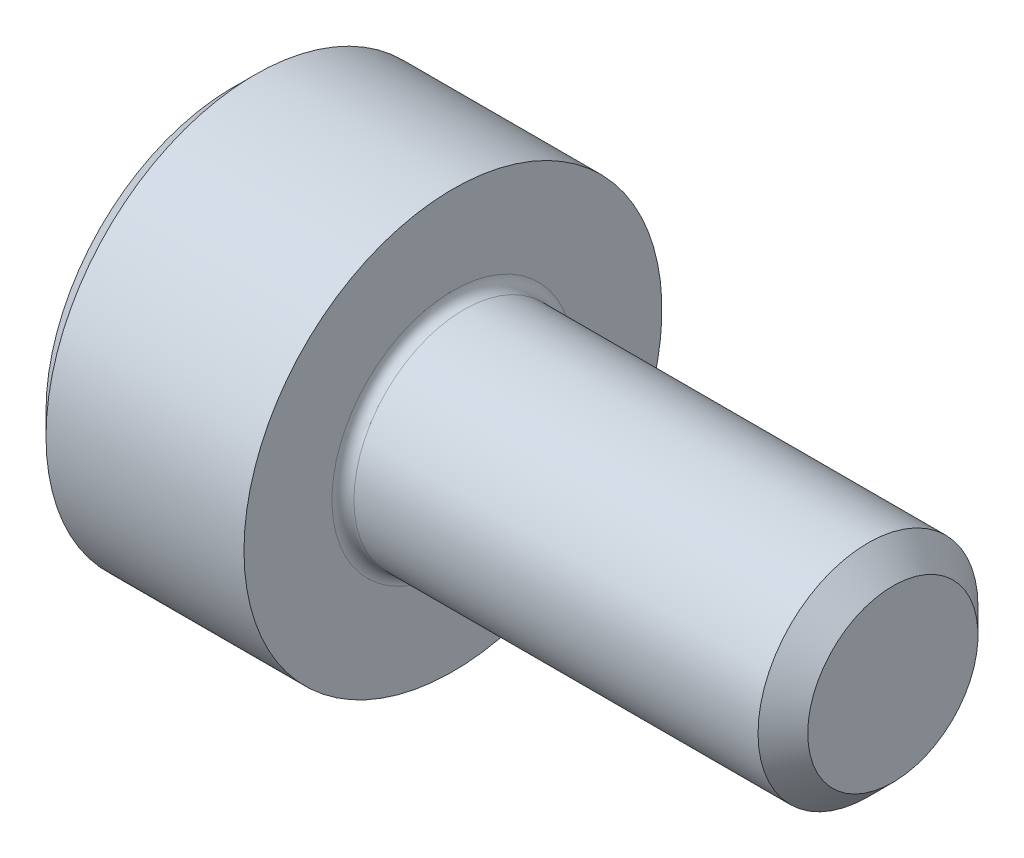
SolidWorks part; units mm, degrees
revolve "Base-Revolve" add sketch "BodySke"
sketch "BodySke" plane through (0, 0, 0) normal (0, 0, 1) x (1, 0, 0)
  line L0 (0, 0) -> (0, 1.7)
  line L1 (0.2, 1.9) -> (2, 1.9)
  line L2 (2, 1.9) -> (2, 1)
  line L3 (2, 1) -> (5.774, 1)
  line L4 (6, 0.774) -> (6, 0)
  line L5 (6, 0) -> (0, 0)
  line L6 (-31.75, 0) -> (127, 0) construction
  line L7 (0, 1.7) -> (0.2, 1.9)
  line L8 (6, 0.774) -> (5.774, 1)
  line L9 (0, -1.7) -> (0.2, -1.9) construction
  line L10 (6, -0.774) -> (5.774, -1) construction
  line L11 (2.4, 9.525) -> (2.4, 3.175) construction
  line L12 (2, 9.525) -> (2, 3.175) construction
  line L13 (-44, 9.525) -> (-44, 3.175) construction
  dimension "Diameter" = 2
  dimension "Head_ht" = 2
  dimension "Length" = 4
  dimension "Body_ch_ang" = 45
  dimension "Head_dia" = 3.8
  dimension "Head_ch_ang" = 45
  dimension "Minor_dia" = 1.548
  dimension "Advance" = 0.4
  dimension "Thread_nom" = 4
  dimension "Thread_length" = 50
  dimension "Head_ch_ht" = 0.2
cosmetic thread "ThreadCosmetic" [suppressed]
fillet "Fillet1" radius 0.1 1 edges at (2, 0, 1)
ref_plane "Plane1" through (0, 0, 0) normal (0, 0, 1) x (1, 0, 0)
ref_plane "Plane2" through (0, 0, 0) normal (0, 1, 0) x (1, 0, 0)
ref_plane "Plane3" through (0, 0, 0) normal (1, 0, 0) x (0, 0, -1)
sketch "Sketch2" plane through (0, 0, 0) normal (0, 0, 1) x (1, 0, 0)
  line L0 (0, 0.7725) -> (1, 0.7725)
  line L1 (1, 0.7725) -> (1.446, 0)
  line L2 (-31.75, 0) -> (127, 0) construction
  line L3 (1.446, 0) -> (0, 0)
  line L4 (0, 0) -> (0, 0.7725)
  line L5 (0, 1.7) -> (0, -1.7) construction
  line L6 (0, 0) -> (47.625, 0) construction
  line L7 (2, -1.9) -> (2, 1.9) construction
  dimension "D1" = 0.7725
  dimension "D2" = 60
revolve "Hex-PreBroach" cut sketch "Sketch2" angle 360 about L6
sketch "Sketch3" plane through (0, 0, 0) normal (-1, 0, 0) x (0, 0.5, 0.866)
  line L0 (0.446, 0.7725) -> (-0.446, 0.7725)
  line L1 (-0.446, 0.7725) -> (-0.892, 0)
  line L2 (0.446, 0.7725) -> (0.892, 0)
  line L3 (0.446, -0.7725) -> (0.892, 0)
  line L4 (0.446, -0.7725) -> (-0.446, -0.7725)
  line L5 (-0.446, -0.7725) -> (-0.892, 0)
  dimension "D1" = 0.7725
  dimension "D2" = 0.7725
  dimension "Hex_size" = 1.545
extrude "Hex" cut sketch "Sketch3" against normal blind 1
sketch "Sketch4" plane through (0, 0, 0) normal (-1, 0, 0) x (0, 0, 1)
  line L0 (0, 0) -> (0.9398, 0)
  line L1 (0, 0) -> (6.1484, 3.5498) construction
  line L2 (0, 0) -> (0.4699, 0.8139)
  line L3 (0.7832, 0.2175) -> (0.8962, 0.2828)
  line L4 (0.58, 0.5695) -> (0.693, 0.6348)
  arc A0 (0.7832, 0.2175) -> (0.58, 0.5695) centre (0, 0) ccw
  arc A1 (0.9398, 0) -> (0.8962, 0.2828) centre (0, 0) ccw
  arc A2 (0.4699, 0.8139) -> (0.693, 0.6348) centre (0, 0) cw
  dimension "D1" = 30
  dimension "D2" = 60
  dimension "Spline_p_dim" = 0.4064
  dimension "D3" = 0.2032
extrude "Spline" [suppressed] cut sketch "Sketch4" against normal blind 1
pattern_circular "CirPattern1" [suppressed] count 6 every 60
sketch "Sketch5" plane through (0, 0, 0) normal (0, 0, 1) x (1, 0, 0)
  line L0 (-31.75, 0) -> (127, 0) construction
  line L2 (0, 1.7) -> (0, -1.7) construction
  circle A0 centre (0.1, 0) radius 0.005
  dimension "Drilled_hole_dia" = 0.01
  dimension "Drilled_hole_loc" = 0.1
extrude "Hole" [suppressed] cut sketch "Sketch5" against normal through all and the other way through all
pattern_circular "Drilled-4" [suppressed] count 2 every 60
pattern_circular "Drilled-6" [suppressed] count 3 every 60
sketch "ThdSchSke" plane through (0, 0, 0) normal (0, 0, 1) x (1, 0, 0)
  line L0 (2.4, -0.774) -> (2.2418, -1)
  line L1 (2.4, -0.774) -> (2.5582, -1)
  line L2 (2.5582, -1) -> (2.5582, -1.25)
  line L3 (-3.175, 0) -> (5.1513, 0) construction
  line L5 (2.5582, -1.25) -> (2.2418, -1.25)
  line L6 (2.2418, -1.25) -> (2.2418, -1)
  line L7 (0, 1.7) -> (0, -1.7) construction
  dimension "Thread_minor" = 1.548
  dimension "Diameter" = 2
  dimension "Start" = 2.4
revolve "ThreadSchematic" [suppressed] cut sketch "ThdSchSke" angle 360 about L3
pattern_linear "ThdSchPat" [suppressed]
equation "\"D2@Sketch3\" = \"Hex_size@Sketch3\" / 2"
equation "\"D1@Sketch3\" = \"Hex_size@Sketch3\" / 2"
equation "\"D1@Sketch2\" = \"Hex_size@Sketch3\" / 2"
equation "\"D3@Sketch4\" = \"Spline_p_dim@Sketch4\" / 2"
equation "\"Thread_minor@ThreadCosmetic\"  =  \"Minor_dia@BodySke\""
equation "\"D2@CirPattern1\" = 360 / \"Num_teeth@CirPattern1\""
equation "\"Wall_thickness@Sketch2\" = \"Head_ht@BodySke\" - \"Key_eng@Hex\""
equation "\"Thread_length@ThreadCosmetic\" = ((sgn( (\"Length@BodySke\" - \"Advance@BodySke\" ) - \"Thread_nom@BodySke\" )-1)*( (\"Length@BodySke\" - \"Advance@BodySke\" ) - \"Thread_nom@BodySke\" ))/-2+ \"Thread_nom@BodySke\""
equation "\"Thread_minor@ThdSchSke\" = \"Minor_dia@BodySke\""
equation "\"Diameter@ThdSchSke\" = \"Diameter@BodySke\""
equation "\"Overcut@ThdSchSke\" = \"Diameter@BodySke\" * 1.25"
equation "\"Start@ThdSchSke\" = \"Head_ht@BodySke\" + \"Length@BodySke\" - \"Thread_length@ThreadCosmetic\"  '---Non-countersunk---"
equation "\"Num_threads@ThdSchPat\" = int( \"Thread_length@ThreadCosmetic\" / \"Advance@BodySke\" + 0.999 )  + 1"
equation "\"Advance@ThdSchPat\" = \"Thread_length@ThreadCosmetic\" /  (\"Num_threads@ThdSchPat\" - 1) 'relax it"
equation "\"Num_threads@ThdSchPat\" = \"Num_threads@ThdSchPat\" - sgn( \"Num_threads@ThdSchPat\" - 1) '---chamfered tips only---"
